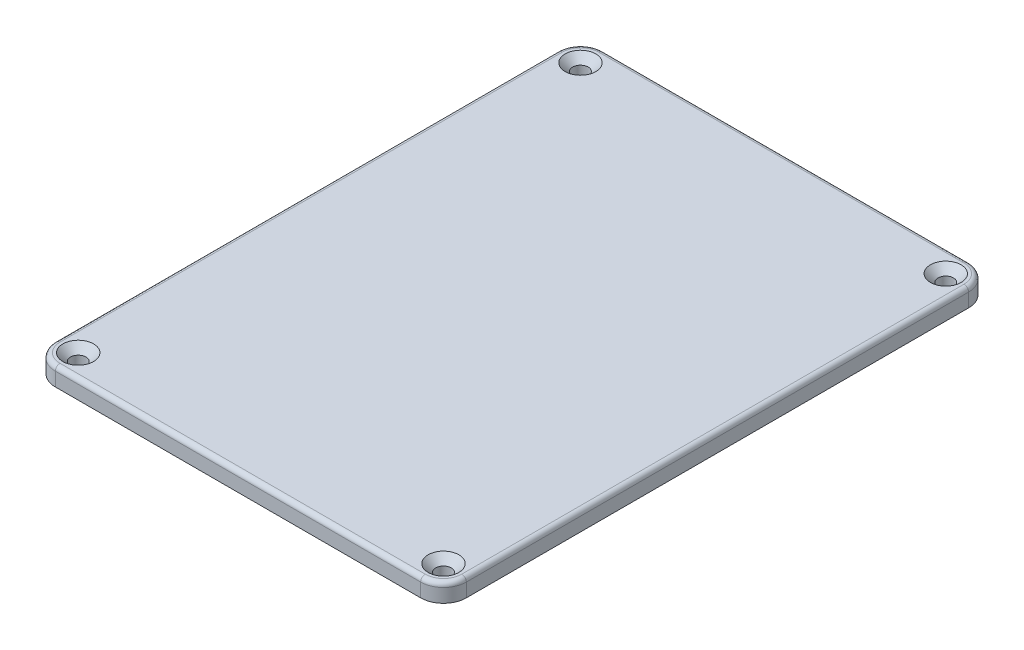
SolidWorks part; units mm, degrees
ref_plane "前视基准面" through (0, 0, 0) normal (0, 0, 1) x (1, 0, 0)
ref_plane "上视基准面" through (0, 0, 0) normal (0, 1, 0) x (1, 0, 0)
ref_plane "右视基准面" through (0, 0, 0) normal (1, 0, 0) x (0, 0, -1)
sketch "草图2" plane through (0, 0, 0) normal (0, 1, 0) x (1, 0, 0)
  line L1 (-45, 60) -> (45, 60)
  line L2 (-45, 60) -> (-45, -60)
  line L3 (-45, -60) -> (45, -60)
  line L4 (45, 60) -> (45, -60)
  line L5 (0, -60) -> (0, 60) construction
  line L6 (-45, 0) -> (45, 0) construction
  point P0 (0, 0)
  dimension "D1" = 120
  dimension "D2" = 90
extrude "凸台-拉伸1" add sketch "草图2" along normal blind 3
sketch "草图3" plane through (0, 0, 0) normal (0, -1, 0) x (1, 0, 0)
  line L0 (-42, -50) -> (-42, 50)
  line L1 (-35, -57) -> (35, -57)
  line L3 (-45, 60) -> (45, 60)
  line L4 (42, -50) -> (42, 50)
  line L5 (0, 51.4771) -> (0, -51.4771) construction
  line L6 (-40, 0) -> (40, 0) construction
  line L7 (-45, 60) -> (-45, -60)
  line L8 (-45, -60) -> (45, -60)
  line L9 (-42, 50) -> (-35, 50)
  line L10 (-35, 57) -> (-35, 50)
  line L11 (45, 60) -> (45, -60)
  line L12 (0, -60) -> (0, 60) construction
  line L13 (42, 50) -> (35, 50)
  line L14 (35, 57) -> (35, 50)
  line L15 (-45, 0) -> (45, 0) construction
  line L17 (42, -50) -> (35, -50)
  line L18 (35, -57) -> (35, -50)
  line L21 (-42, -50) -> (-35, -50)
  line L22 (-35, -57) -> (-35, -50)
  line L23 (-35, 57) -> (35, 57)
  line L27 (0, 60) -> (0, -60) construction
  line L28 (-45, 0) -> (45, 0) construction
  line L33 (0, -60) -> (0, 60) construction
  line L34 (45, 0) -> (-45, 0) construction
  point P0 (0, 0)
  point P1 (0, 0)
  point P4 (0, 0)
  point P34 (0, 0)
  dimension "D11" = 7
  dimension "D1" = 120
  dimension "D2" = 90
  dimension "D3" = 7
  dimension "D4" = 7
  dimension "D5" = 3
  dimension "D6" = 7
  dimension "D7" = 7
  dimension "D8" = 3
  dimension "D9" = 7
  dimension "D10" = 7
  dimension "D12" = 7
  dimension "D13" = 3
  dimension "D14" = 7
extrude "凸台-拉伸2" add sketch "草图3" along normal blind 1 separate body
hole_wizard "M3 六角凹锥坑螺钉的锥形沉头孔3" positions "草图14" profile "草图15" countersink size "M3" standard "ISO" end condition through all
sketch "草图14" plane through (0, 3, 0) normal (0, 1, 0) x (1, 0, 0)
  line L0 (-45, -60) -> (45, -60) construction
  line L3 (45, -60) -> (45, 60) construction
  line L4 (-45, 60) -> (-45, -60) construction
  line L5 (45, 60) -> (-45, 60) construction
  point P0 (-40, -55)
  point P2 (-40, 55)
  point P4 (40, 55)
  point P6 (40, -55)
  dimension "D1" = 5
  dimension "D2" = 5
  dimension "D3" = 5
  dimension "D4" = 5
  dimension "D5" = 5
  dimension "D6" = 5
  dimension "D7" = 5
  dimension "D8" = 5
sketch "草图15" plane through (-40, 3, 55) normal (1, 0, 0) x (0, 0, 1)
  line L0 (0, 0) -> (0, 4)
  line L1 (0, 4) -> (1.7, 4)
  line L2 (1.7, 4) -> (1.7, 1.66)
  line L3 (1.7, 1.66) -> (3.36, 0)
  line L5 (3.36, 0) -> (0, 0)
  line L6 (-1.7, 1.66) -> (-3.36, 0) construction
  line L11 (0, -6.35) -> (0, 107.95) construction
  dimension "通孔孔直径" = 3.4
  dimension "通孔孔深度" = 4
  dimension "近端锥形沉头孔直径" = 6.72
  dimension "近端锥形沉头孔角度" = 90
combine bodies "组合2" operation type add bodies to combine 121 120
fillet "圆角2" radius 5 1 edges at (35, -0.5, -50)
fillet "圆角3" radius 5 1 edges at (-35, -0.5, -50)
fillet "圆角4" radius 5 1 edges at (35, -0.5, 50)
fillet "圆角5" radius 5 1 edges at (-35, -0.5, 50)
fillet "圆角6" radius 5 1 edges at (-45, 1, -60)
fillet "圆角7" radius 5 1 edges at (45, 1, -60)
fillet "圆角8" radius 5 1 edges at (45, 1, 60)
fillet "圆角9" radius 5 1 edges at (-45, 1, 60)
fillet "圆角11" radius 1 8 edges at (-43.5355, 3, 58.5355) (-45, 3, 0) (-43.5355, 3, -58.5355) (0, 3, -60) (43.5355, 3, -58.5355) (45, 3, 0) (43.5355, 3, 58.5355) (0, 3, 60)
sketch "草图18" plane through (0, 0, 0) normal (0, -1, 0) x (1, 0, 0)
  line L1 (-42, 50) -> (-42, -50) construction
  line L2 (42, -50) -> (42, 50) construction
  line L3 (40, -50) -> (42, -50) construction
  line L4 (-42, -50) -> (-40, -50) construction
  line L5 (-35, -57) -> (35, -57) construction
  circle A1 centre (-37, 29) radius 3
  circle A5 centre (37, 29) radius 3
  circle A7 centre (0, 18) radius 3
  circle A15 centre (-37, -41) radius 3
  circle A17 centre (37, -41) radius 3
  dimension "D1" = 75
  dimension "D2" = 5
  dimension "D3" = 5
  dimension "D4" = 5
  dimension "D5" = 9
  dimension "D6" = 9
  dimension "D7" = 86
  dimension "D8" = 86
  dimension "D9" = 42
  dimension "D10" = 5
extrude "凸台-拉伸5" add sketch "草图18" along normal blind 1
sketch "草图19" plane through (0, -1, 0) normal (0, -1, 0) x (1, 0, 0)
  circle A2 centre (-37, 29) radius 2
  circle A4 centre (37, 29) radius 2
  circle A5 centre (0, 18) radius 2
  circle A7 centre (-37, -41) radius 2
  circle A8 centre (37, -41) radius 2
extrude "切除-拉伸1" cut sketch "草图19" against normal blind 3.1
